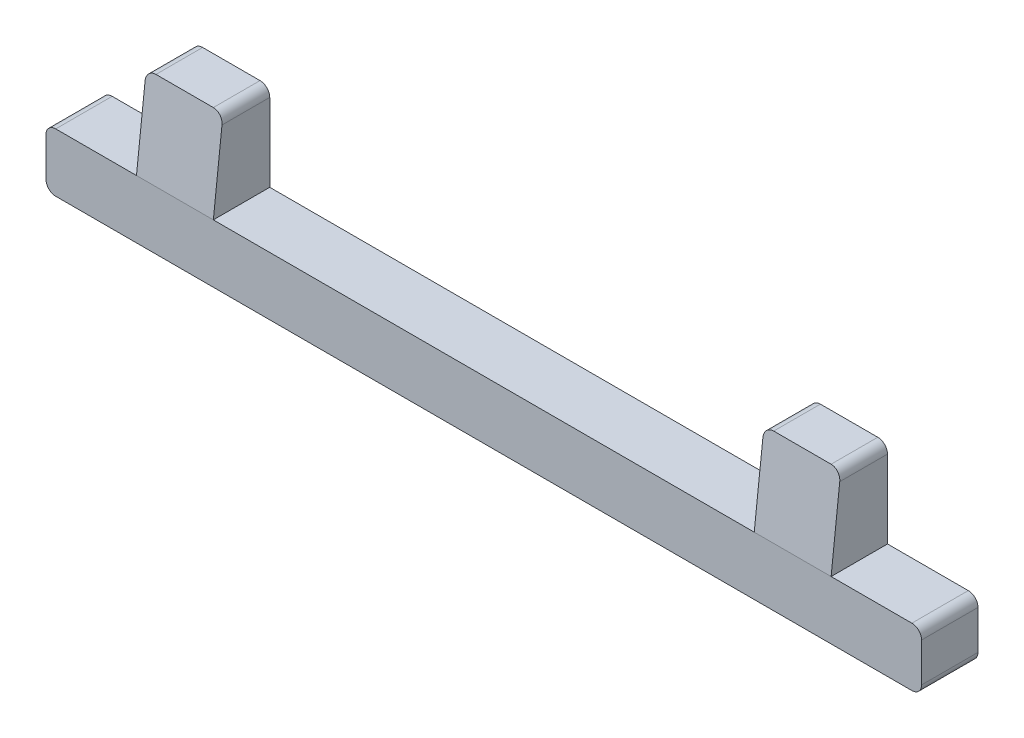
SolidWorks part; units mm, degrees
ref_plane "Front Plane" through (0, 0, 0) normal (0, 0, 1) x (1, 0, 0)
ref_plane "Top Plane" through (0, 0, 0) normal (0, 1, 0) x (1, 0, 0)
ref_plane "Right Plane" through (0, 0, 0) normal (1, 0, 0) x (0, 0, -1)
sketch "Sketch1" plane through (0, 0, 0) normal (0, 0, 1) x (1, 0, 0)
  line L0 (0, 0) -> (90, 0)
  line L1 (90, 0) -> (90, 6)
  line L2 (90, 6) -> (80.7, 6)
  line L3 (80.7, 6) -> (80.7, 15)
  line L4 (80.7, 15) -> (72.8, 15)
  line L5 (72.8, 15) -> (72.8, 6)
  line L6 (72.8, 6) -> (17.2, 6)
  line L7 (17.2, 6) -> (17.2, 15)
  line L8 (17.2, 15) -> (9.3, 15)
  line L9 (9.3, 15) -> (9.3, 6)
  line L10 (9.3, 6) -> (0, 6)
  line L11 (0, 6) -> (0, 0)
  circle A0 centre (13.25, 3) radius 1.25 construction
  circle A1 centre (76.75, 3) radius 1.25 construction
  point P17 (0, 0)
  point P18 (0, 3)
  point P19 (13.25, 15)
  point P20 (76.75, 15)
  dimension "D6" = 2.5
  dimension "D1" = 55.6
  dimension "D2" = 71.4
  dimension "D3" = 90
  dimension "D4" = 6
  dimension "D5" = 9
extrude "Boss-Extrude1" add sketch "Sketch1" along normal blind 5.8
sketch "Sketch2" plane through (80.7, 0, 0) normal (1, 0, 0) x (0, 0, -1)
  line L0 (-5.8, 15) -> (-5.8, 6)
  line L1 (-5.8, 6) -> (-4.8, 15)
  line L2 (-5.8, 15) -> (0, 15) construction
  line L3 (-4.8, 15) -> (-5.8, 15)
  dimension "D1" = 1
extrude "Cut-Extrude1" cut sketch "Sketch2" against normal through all
fillet "Fillet1" radius 1 8 edges at (0, 0, 2.9) (90, 0, 2.9) (90, 6, 2.9) (80.7, 15, 2.4) (72.8, 15, 2.4) (17.2, 15, 2.4) (0, 6, 2.9) (9.3, 15, 2.4)
